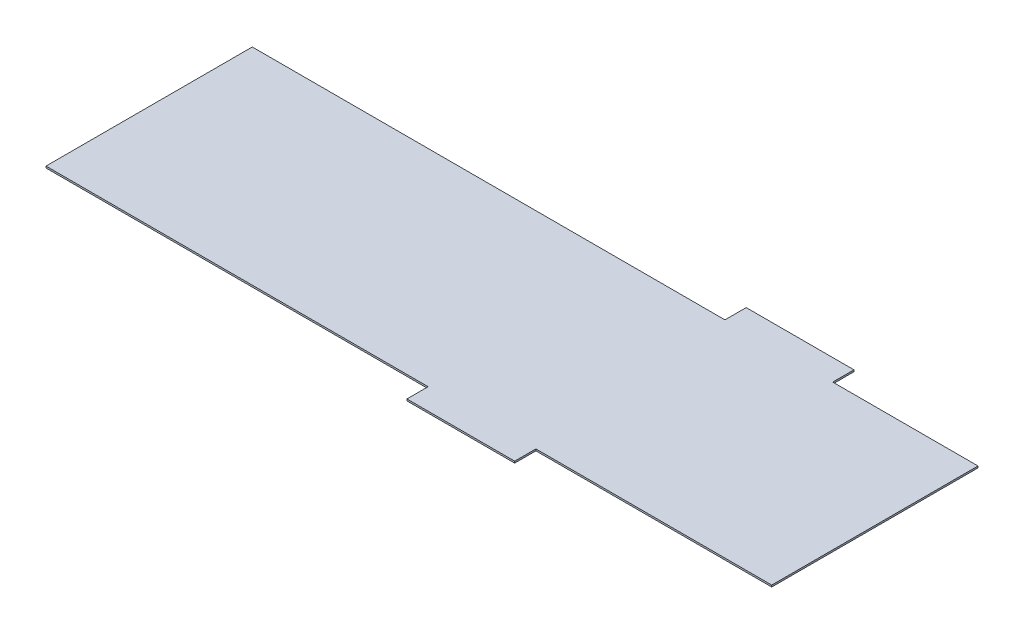
SolidWorks part; units mm, degrees
ref_plane "Front Plane" through (0, 0, 0) normal (0, 0, 1) x (1, 0, 0)
ref_plane "Top Plane" through (0, 0, 0) normal (0, 1, 0) x (1, 0, 0)
ref_plane "Right Plane" through (0, 0, 0) normal (1, 0, 0) x (0, 0, -1)
sketch "Sketch1" plane through (0, 287.2352, 0) normal (0, -1, 0) x (1, 0, 0)
  line L0 (295.5772, 2393.1549) -> (-319.3738, 2393.1549) construction
  line L1 (-2540.4228, 2443.1549) -> (1668.0972, 2443.1549)
  line L2 (-2540.4228, 2443.1549) -> (-2540.4228, 1246.9486)
  line L3 (-2540.4228, 1246.9486) -> (1668.0972, 1246.9486)
  line L4 (1668.0972, 2443.1549) -> (1668.0972, 1246.9486)
  line L5 (205.5772, 1296.9486) -> (820.5282, 1296.9486) construction
  line L6 (1175.5772, 2009.9506) -> (1175.5772, 1679.9506) construction
  line L7 (-674.4228, 2014.9506) -> (-674.4228, 1674.9506) construction
  dimension "D1" = 50
  dimension "D2" = 50
  dimension "D3" = 492.52
  dimension "D4" = 1866
extrude "Bottom plate" add sketch "Sketch1" along normal blind 10
sketch "Sketch4" plane through (0, 277.2352, 0) normal (0, -1, 0) x (1, 0, 0)
  line L0 (1668.0972, 2443.1549) -> (-2540.4228, 2443.1549) construction
  line L1 (-319.3738, 2561.1549) -> (295.5772, 2561.1549) construction
  line L2 (-319.3738, 2561.1549) -> (-319.3738, 2443.1549) construction
  line L3 (-319.3738, 2443.1549) -> (295.5772, 2443.1549) construction
  line L4 (295.5772, 2561.1549) -> (295.5772, 2443.1549) construction
  line L5 (295.5772, 2218.1529) -> (295.5772, 2561.1549) construction
  line L6 (-2540.4228, 1246.9486) -> (1668.0972, 1246.9486) construction
  line L7 (205.5772, 1246.9486) -> (820.5282, 1246.9486) construction
  line L8 (205.5772, 1246.9486) -> (205.5772, 1128.7463) construction
  line L9 (205.5772, 1128.7463) -> (820.5282, 1128.7463) construction
  line L10 (820.5282, 1246.9486) -> (820.5282, 1128.7463) construction
  line L11 (205.5772, 1471.7483) -> (205.5772, 1128.7463) construction
  line L12 (200.5772, 1251.9486) -> (200.5772, 1123.7463)
  line L13 (200.5772, 1123.7463) -> (825.5282, 1123.7463)
  line L14 (825.5282, 1251.9486) -> (825.5282, 1123.7463)
  line L15 (200.5772, 1251.9486) -> (825.5282, 1251.9486)
  line L16 (-324.3738, 2566.1549) -> (-324.3738, 2438.1549)
  line L17 (-324.3738, 2438.1549) -> (300.5772, 2438.1549)
  line L18 (300.5772, 2566.1549) -> (300.5772, 2438.1549)
  line L19 (-324.3738, 2566.1549) -> (300.5772, 2566.1549)
  dimension "D1" = 5
  dimension "D2" = 5
extrude "Plate extension for elevator mechanism" add sketch "Sketch4" against normal up to surface (10 mm away) up to face at (-436.1628, 287.2352, 1845.0518)
